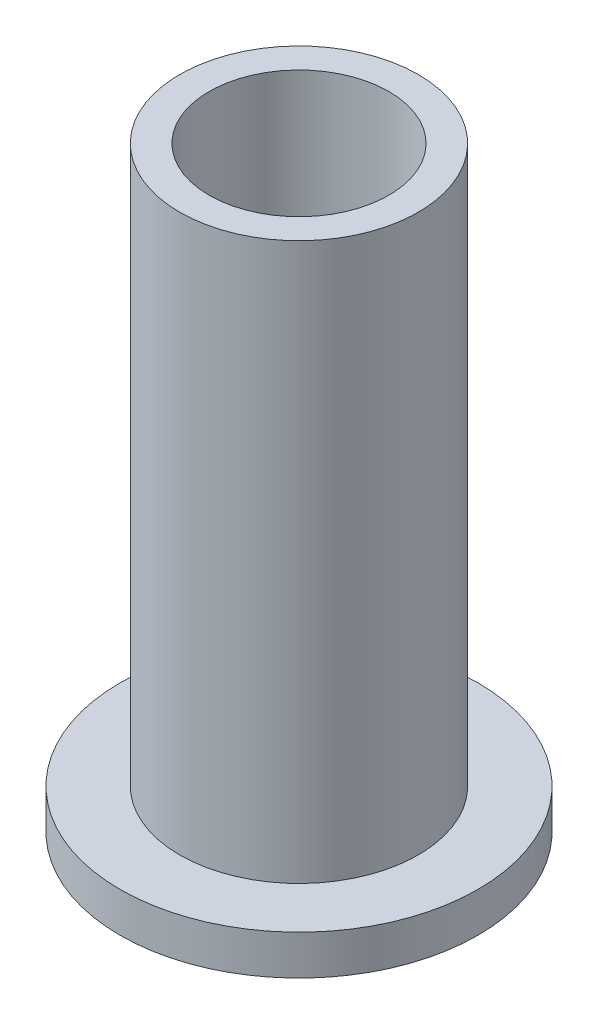
SolidWorks part; units mm, degrees
ref_plane "Front Plane" through (0, 0, 0) normal (0, 0, 1) x (1, 0, 0)
ref_plane "Top Plane" through (0, 0, 0) normal (0, 1, 0) x (1, 0, 0)
ref_plane "Right Plane" through (0, 0, 0) normal (1, 0, 0) x (0, 0, -1)
sketch "Sketch1" plane through (0, 0, 0) normal (0, 1, 0) x (1, 0, 0)
  line L0 (-1.7, 7.3708) -> (1.7, 7.3708) construction
  line L1 (0, 7.3708) -> (0, -4.9377) construction
  line L2 (4.5211, -1.3709) -> (-4.5211, -1.3709) construction
  circle A0 centre (0, -1.3709) radius 4.5211
  circle A1 centre (0, -1.3709) radius 5.9999
extrude "Boss-Extrude1" add sketch "Sketch1" along normal blind 30
sketch "Sketch3" plane through (0, 0, 0) normal (0, -1, 0) x (1, 0, 0)
  circle A1 centre (0, 1.3709) radius 5.9999 construction
  circle A2 centre (0, 1.3709) radius 8.9999
  circle A3 centre (0, 1.3709) radius 8.9999
  circle A4 centre (0, 1.3709) radius 5.9999
  dimension "D1" = 3
extrude "Boss-Extrude2" add sketch "Sketch3" against normal blind 2
